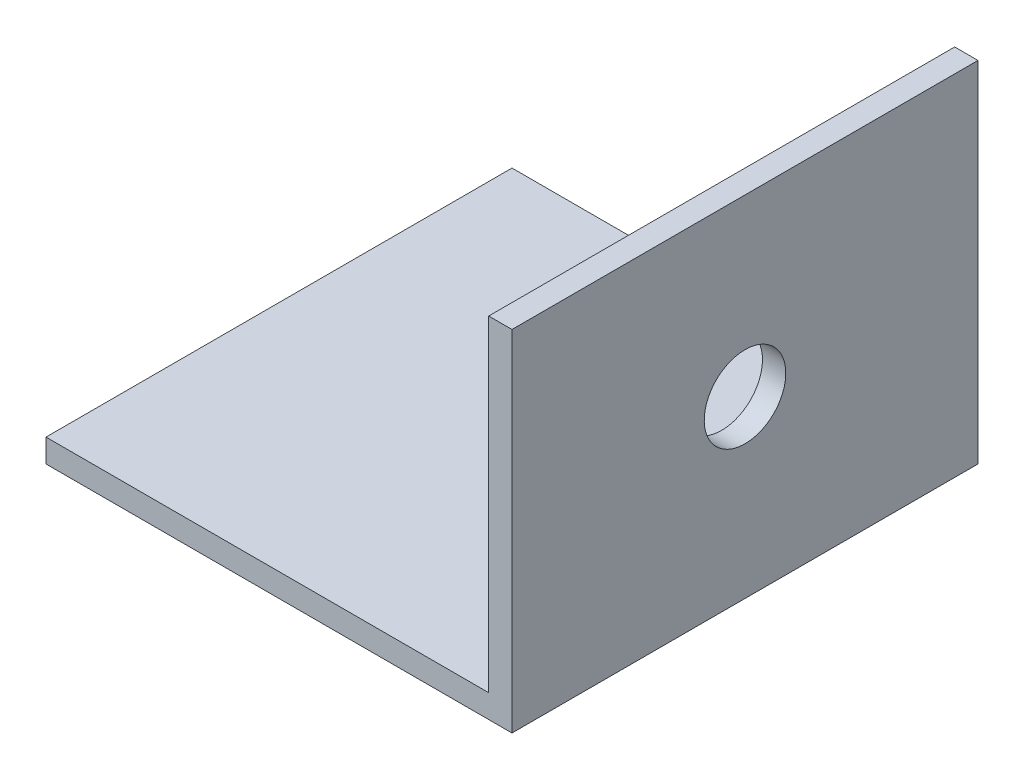
SolidWorks part; units mm, degrees
material "5454-H32"
ref_plane "Alzado" through (0, 0, 0) normal (0, 0, 1) x (1, 0, 0)
ref_plane "Planta" through (0, 0, 0) normal (0, 1, 0) x (1, 0, 0)
ref_plane "Vista lateral" through (0, 0, 0) normal (1, 0, 0) x (0, 0, -1)
sketch "Croquis1" plane through (0, 0, 0) normal (0, 0, 1) x (1, 0, 0)
  line L0 (0.5514, 28.1831) -> (0.5514, -1.8169)
  line L1 (0.5514, 28.1831) -> (-1.4486, 28.1831)
  line L2 (-1.4486, 28.1831) -> (-1.4486, 0.1831)
  line L3 (-1.4486, 0.1831) -> (-39.4486, 0.1831)
  line L4 (-39.4486, 0.1831) -> (-39.4486, -1.8169)
  line L5 (-39.4486, -1.8169) -> (0.5514, -1.8169)
  dimension "D1" = 2
  dimension "D2" = 30
  dimension "D3" = 40
extrude "Saliente-Extruir1" add sketch "Croquis1" along normal blind 40
sketch "Croquis2" plane through (0.5514, 0, 0) normal (1, 0, 0) x (0, 0, -1)
  line L0 (-40, 28.1831) -> (0, -1.8169) construction
  circle A0 centre (-20, 13.1831) radius 3.5
  dimension "D1" = 7
extrude "Cortar-Extruir1" cut sketch "Croquis2" against normal through all
